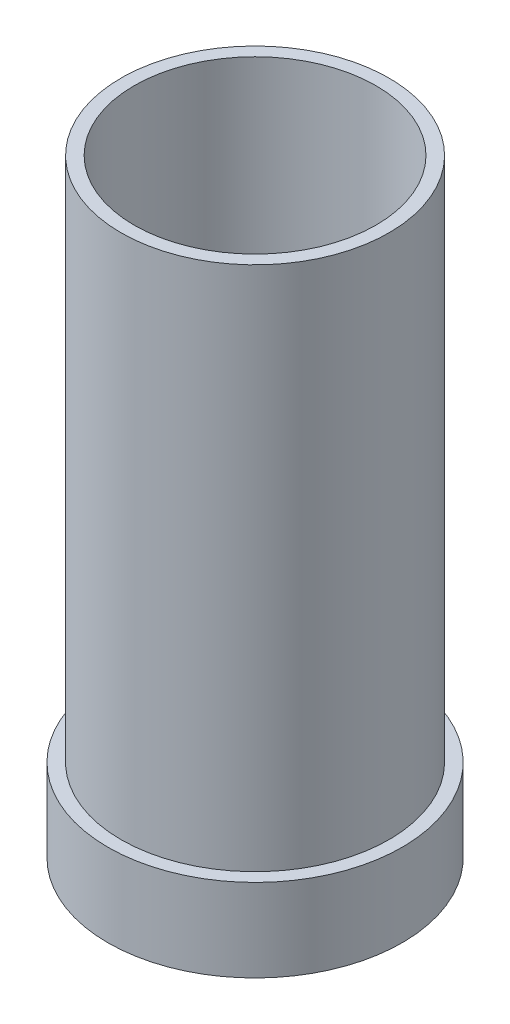
SolidWorks part; units mm, degrees
ref_plane "Front Plane" through (0, 0, 0) normal (0, 0, 1) x (1, 0, 0)
ref_plane "Top Plane" through (0, 0, 0) normal (0, 1, 0) x (1, 0, 0)
ref_plane "Right Plane" through (0, 0, 0) normal (1, 0, 0) x (0, 0, -1)
sketch "Sketch1" plane through (0, 0, 0) normal (0, 1, 0) x (1, 0, 0)
  circle A0 centre (0, 0) radius 3.556
  dimension "D1" = 7.112
extrude "Boss-Extrude1" add sketch "Sketch1" along normal blind 2
sketch "Sketch2" plane through (0, 2, 0) normal (0, 1, 0) x (1, 0, 0)
  circle A0 centre (0, 0) radius 3.2385
  dimension "D1" = 6.477
extrude "Boss-Extrude2" add sketch "Sketch2" along normal blind 12.7
sketch "Sketch3" plane through (0, 14.7, 0) normal (0, 1, 0) x (1, 0, 0)
  circle A0 centre (0, 0) radius 2.921
  dimension "D1" = 5.842
extrude "Cut-Extrude1" cut sketch "Sketch3" against normal blind 12.7
